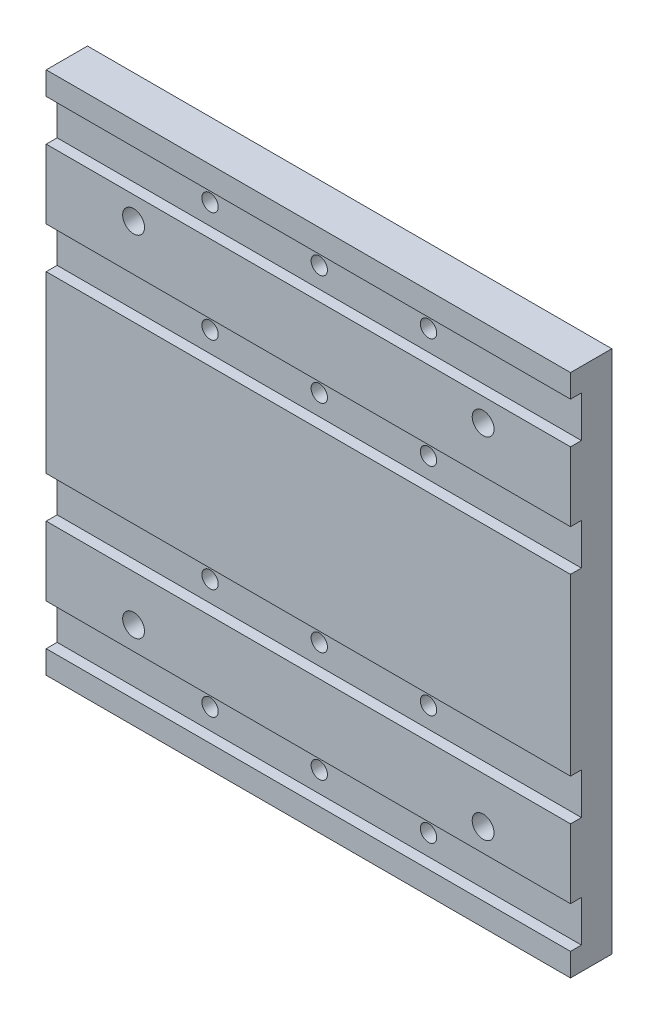
SolidWorks part; units mm, degrees
ref_plane "Front Plane" through (0, 0, 0) normal (0, 0, 1) x (1, 0, 0)
ref_plane "Top Plane" through (0, 0, 0) normal (0, 1, 0) x (1, 0, 0)
ref_plane "Right Plane" through (0, 0, 0) normal (1, 0, 0) x (0, 0, -1)
sketch "Sketch1" plane through (0, 0, 0) normal (0, 0, 1) x (1, 0, 0)
  line L1 (-76.2, 76.2) -> (76.2, 76.2)
  line L2 (-76.2, 76.2) -> (-76.2, -76.2)
  line L3 (-76.2, -76.2) -> (76.2, -76.2)
  line L4 (76.2, 76.2) -> (76.2, -76.2)
  line L5 (-76.2, 76.2) -> (76.2, -76.2) construction
  line L6 (-76.2, -76.2) -> (76.2, 76.2) construction
  circle A0 centre (-50.8, 50.8) radius 3.175
  circle A1 centre (-50.8, -50.8) radius 3.175
  circle A2 centre (50.8, 50.8) radius 3.175
  circle A3 centre (50.8, -50.8) radius 3.175
  point P0 (0, 0)
  dimension "D5" = 6.35
  dimension "D6" = 6.35
  dimension "D7" = 6.35
  dimension "D8" = 6.35
  dimension "D9" = 25.4
  dimension "D10" = 25.4
  dimension "D11" = 25.4
  dimension "D12" = 25.4
  dimension "D13" = 25.4
  dimension "D14" = 25.4
  dimension "D15" = 25.4
  dimension "D16" = 101.6
  dimension "D1" = 0
  dimension "D2" = 0
  dimension "D3" = 152.4
  dimension "D4" = 152.4
extrude "Boss-Extrude1" add sketch "Sketch1" along normal blind 12
sketch "Sketch2" plane through (0, 0, 12) normal (0, 0, 1) x (1, 0, 0)
  line L0 (76.2, -76.2) -> (76.2, 76.2) construction
  line L1 (-76.2, -25.4) -> (76.2, -25.4)
  line L2 (-76.2, -25.4) -> (-76.2, -37.4)
  line L3 (-76.2, -37.4) -> (76.2, -37.4)
  line L4 (76.2, -25.4) -> (76.2, -37.4)
  line L5 (-76.2, -25.4) -> (76.2, -37.4) construction
  line L6 (-76.2, -37.4) -> (76.2, -25.4) construction
  line L7 (-76.2, 37.4) -> (76.2, 37.4)
  line L8 (-76.2, 37.4) -> (-76.2, 25.4)
  line L9 (-76.2, 25.4) -> (76.2, 25.4)
  line L10 (76.2, 37.4) -> (76.2, 25.4)
  line L11 (-76.2, 37.4) -> (76.2, 25.4) construction
  line L12 (-76.2, 25.4) -> (76.2, 37.4) construction
  line L13 (-76.2, 69.5) -> (76.2, 69.5)
  line L14 (-76.2, 69.5) -> (-76.2, 57.5)
  line L15 (-76.2, 57.5) -> (76.2, 57.5)
  line L16 (76.2, 69.5) -> (76.2, 57.5)
  line L17 (-76.2, 69.5) -> (76.2, 57.5) construction
  line L18 (-76.2, 57.5) -> (76.2, 69.5) construction
  line L19 (-76.2, -57.5) -> (76.2, -57.5)
  line L20 (-76.2, -57.5) -> (-76.2, -69.5)
  line L21 (-76.2, -69.5) -> (76.2, -69.5)
  line L22 (76.2, -57.5) -> (76.2, -69.5)
  line L23 (-76.2, -57.5) -> (76.2, -69.5) construction
  line L24 (-76.2, -69.5) -> (76.2, -57.5) construction
  line L25 (-76.2, -76.2) -> (76.2, -76.2) construction
  line L26 (76.2, 76.2) -> (-76.2, 76.2) construction
  line L27 (-76.2, 76.2) -> (-76.2, -76.2) construction
  circle A0 centre (-31.75, 63.5) radius 2.3812
  circle A1 centre (0, 63.5) radius 2.3812
  circle A2 centre (0, -63.5) radius 2.3813
  circle A3 centre (0, -31.4) radius 2.3813
  circle A4 centre (0, 31.4) radius 2.3812
  circle A5 centre (31.75, 31.4) radius 2.3812
  circle A6 centre (-31.75, 31.4) radius 2.3812
  circle A7 centre (31.75, 63.5) radius 2.3812
  circle A8 centre (-31.75, -63.5) radius 2.3812
  circle A9 centre (31.75, -63.5) radius 2.3812
  circle A10 centre (-31.75, -31.4) radius 2.3812
  circle A11 centre (31.75, -31.4) radius 2.3812
  point P0 (0, -31.4)
  point P5 (0, 31.4)
  point P10 (0, 63.5)
  point P15 (0, -63.5)
  dimension "D18" = 4.7625
  dimension "D19" = 4.7625
  dimension "D20" = 4.7625
  dimension "D21" = 4.7625
  dimension "D22" = 4.7625
  dimension "D23" = 4.7625
  dimension "D24" = 4.7625
  dimension "D25" = 4.7625
  dimension "D28" = 4.7625
  dimension "D31" = 4.7625
  dimension "D17" = 31.75
  dimension "D32" = 31.75
  dimension "D35" = 31.75
  dimension "D37" = 0
  dimension "D40" = 4.7625
  dimension "D41" = 4.7625
  dimension "D45" = 6
  dimension "D46" = 6
  dimension "D1" = 152.4
  dimension "D2" = 12
  dimension "D3" = 0
  dimension "D4" = 152.4
  dimension "D5" = 12
  dimension "D6" = 12.7
  dimension "D7" = 12.7
  dimension "D8" = 0
  dimension "D9" = 152.4
  dimension "D10" = 0
  dimension "D11" = 12
  dimension "D12" = 50.8
  dimension "D13" = 152.4
  dimension "D14" = 12
  dimension "D15" = 50.8
  dimension "D16" = 0
  dimension "D26" = 0
  dimension "D27" = 0
  dimension "D29" = 0
  dimension "D30" = 0
  dimension "D33" = 0
  dimension "D34" = 31.75
  dimension "D36" = 0
  dimension "D38" = 31.75
  dimension "D39" = 31.75
  dimension "D42" = 31.75
  dimension "D43" = 31.75
  dimension "D44" = 6
extrude "Cut-Extrude1" cut sketch "Sketch2" against normal blind 3.175
sketch "Sketch3" plane through (0, 0, 12) normal (0, 0, 1) x (1, 0, 0)
  circle A0 centre (-31.75, 63.5) radius 2.3813
  circle A1 centre (0, 63.5) radius 2.3813
  circle A2 centre (31.75, 63.5) radius 2.3812
  circle A3 centre (-31.75, 31.4) radius 2.3812
  circle A4 centre (0, 31.4) radius 2.3813
  circle A5 centre (31.75, 31.4) radius 2.3813
  circle A6 centre (-31.75, -31.4) radius 2.3812
  circle A7 centre (0, -31.4) radius 2.3813
  circle A8 centre (31.75, -31.4) radius 2.3813
  circle A9 centre (-31.75, -63.5) radius 2.3812
  circle A10 centre (0, -63.5) radius 2.3813
  circle A11 centre (31.75, -63.5) radius 2.3812
extrude "Cut-Extrude2" cut sketch "Sketch3" against normal through all
sketch "Sketch5" plane through (0, 0, 0) normal (0, 0, -1) x (-1, 0, 0)
  circle A0 centre (31.75, -63.5) radius 3.9687
  circle A1 centre (0, -63.5) radius 3.9688
  circle A2 centre (-31.75, -63.5) radius 3.9688
  circle A3 centre (-31.75, -31.4) radius 3.9688
  circle A4 centre (0, -31.4) radius 3.9688
  circle A5 centre (31.75, -31.4) radius 3.9687
  circle A6 centre (31.75, 31.4) radius 3.9687
  circle A7 centre (0, 31.4) radius 3.9688
  circle A8 centre (-31.75, 31.4) radius 3.9688
  circle A9 centre (-31.75, 63.5) radius 3.9688
  circle A10 centre (0, 63.5) radius 3.9687
  circle A11 centre (31.75, 63.5) radius 3.9687
  dimension "D1" = 7.9375
  dimension "D2" = 7.9375
  dimension "D3" = 7.9375
  dimension "D4" = 7.9375
  dimension "D5" = 7.9375
  dimension "D6" = 7.9375
  dimension "D7" = 7.9375
  dimension "D8" = 7.9375
  dimension "D9" = 7.9375
  dimension "D10" = 7.9375
  dimension "D11" = 7.9375
  dimension "D12" = 7.9375
extrude "Cut-Extrude7" cut sketch "Sketch5" against normal blind 5.08
